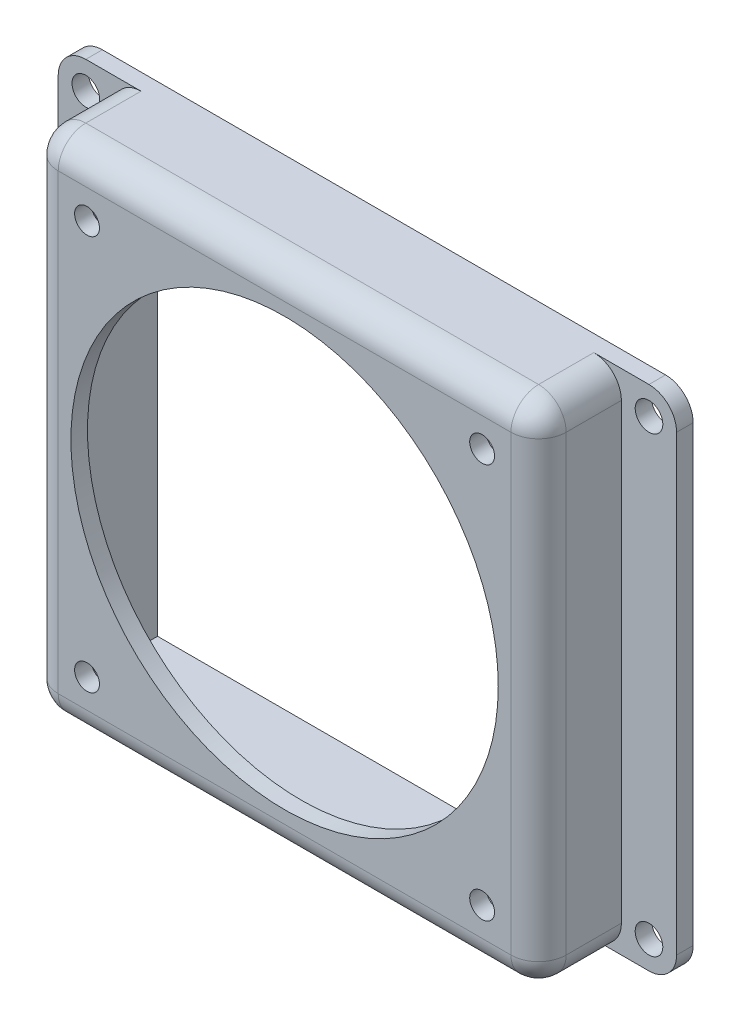
SolidWorks part; units mm, degrees
ref_plane "Front Plane" through (0, 0, 0) normal (0, 0, 1) x (1, 0, 0)
ref_plane "Top Plane" through (0, 0, 0) normal (0, 1, 0) x (1, 0, 0)
ref_plane "Right Plane" through (0, 0, 0) normal (1, 0, 0) x (0, 0, -1)
sketch "Sketch1" plane through (0, 0, 0) normal (0, 0, 1) x (1, 0, 0)
  line L0 (-41, 41) -> (41, 41) construction
  line L1 (-35.78, -35.78) -> (35.78, -35.78) construction
  line L2 (-35.78, -35.78) -> (-35.78, 35.78) construction
  line L3 (-35.78, 35.78) -> (35.78, 35.78) construction
  line L4 (35.78, -35.78) -> (35.78, 35.78) construction
  line L5 (-35.78, -35.78) -> (35.78, 35.78) construction
  line L6 (-35.78, 35.78) -> (35.78, -35.78) construction
  line L7 (-40, -40) -> (40, -40) construction
  line L8 (-40, -40) -> (-40, 40) construction
  line L9 (-40, 40) -> (40, 40) construction
  line L10 (40, -40) -> (40, 40) construction
  line L11 (-40, -40) -> (40, 40) construction
  line L12 (-40, 40) -> (40, -40) construction
  line L13 (41, -41) -> (41, 41) construction
  line L14 (-41, -41) -> (41, -41) construction
  line L15 (-41, -41) -> (-41, 41) construction
  line L16 (-46, 46) -> (46, 46)
  line L17 (46, -46) -> (46, 46)
  line L18 (-46, -46) -> (46, -46)
  line L19 (-46, -46) -> (-46, 46)
  circle A0 centre (0, 0) radius 38.7
  circle A1 centre (-35.78, 35.78) radius 2.25
  circle A2 centre (35.78, 35.78) radius 2.25
  circle A3 centre (35.78, -35.78) radius 2.25
  circle A4 centre (-35.78, -35.78) radius 2.25
  dimension "D1" = 77.4
  dimension "D3" = 4.5
  dimension "D2" = 71.56
  dimension "D4" = 80
  dimension "D5" = 1
  dimension "D6" = 5
extrude "Boss-Extrude1" add sketch "Sketch1" along normal blind 3
sketch "Sketch2" plane through (0, 0, 0) normal (0, 0, -1) x (-1, 0, 0)
  line L0 (41, -41) -> (-41, -41) construction
  line L1 (41, -41) -> (41, 41) construction
  line L2 (41, 41) -> (-41, 41) construction
  line L3 (-41, -41) -> (-41, 41) construction
  line L4 (46, -46) -> (46, 46)
  line L5 (46, 46) -> (-46, 46)
  line L6 (-46, 46) -> (-46, -46)
  line L7 (-46, -46) -> (46, -46)
  line L8 (46, -46) -> (46, 46)
  line L9 (46, 46) -> (-46, 46)
  line L10 (-46, 46) -> (-46, -46)
  line L11 (-46, -46) -> (46, -46)
  line L12 (41, -41) -> (-41, -41)
  line L13 (41, -41) -> (41, 41)
  line L14 (41, 41) -> (-41, 41)
  line L15 (-41, -41) -> (-41, 41)
  dimension "D1" = 0
extrude "Boss-Extrude2" add sketch "Sketch2" along normal blind 15
sketch "Sketch3" plane through (0, 0, -15) normal (0, 0, -1) x (-1, 0, 0)
  line L12 (-51, 41) -> (-56, 41) construction
  line L13 (-46, 46) -> (-56, 46)
  line L14 (-46, 46) -> (-46, -46)
  line L15 (-46, -46) -> (-56, -46)
  line L16 (-56, 46) -> (-56, -46)
  line L17 (46, 46) -> (56, 46)
  line L18 (46, 46) -> (46, -46)
  line L19 (46, -46) -> (56, -46)
  line L20 (56, 46) -> (56, -46)
  line L21 (51, -41) -> (-51, -41) construction
  line L22 (51, -41) -> (51, 41) construction
  line L23 (51, 41) -> (-51, 41) construction
  line L24 (-51, -41) -> (-51, 41) construction
  line L25 (51, -41) -> (-51, 41) construction
  line L26 (51, 41) -> (-51, -41) construction
  line L27 (-51, 46) -> (-51, 41) construction
  circle A0 centre (-51, 41) radius 2.5
  circle A1 centre (51, 41) radius 2.5
  circle A2 centre (51, -41) radius 2.5
  circle A3 centre (-51, -41) radius 2.5
  point P10 (-51, 46)
  point P14 (0, 0)
  dimension "D2" = 5
  dimension "D1" = 10
extrude "Boss-Extrude3" add sketch "Sketch3" against normal blind 3
fillet "Fillet1" radius 5 12 edges at (-46, 0, 3) (0, 46, 3) (46, 0, 3) (0, -46, 3) (-46, -46, -4.5) (-46, 46, -4.5) (46, 46, -4.5) (46, -46, -4.5) (-56, 46, -13.5) (-56, -46, -13.5) (56, 46, -13.5) (56, -46, -13.5)
